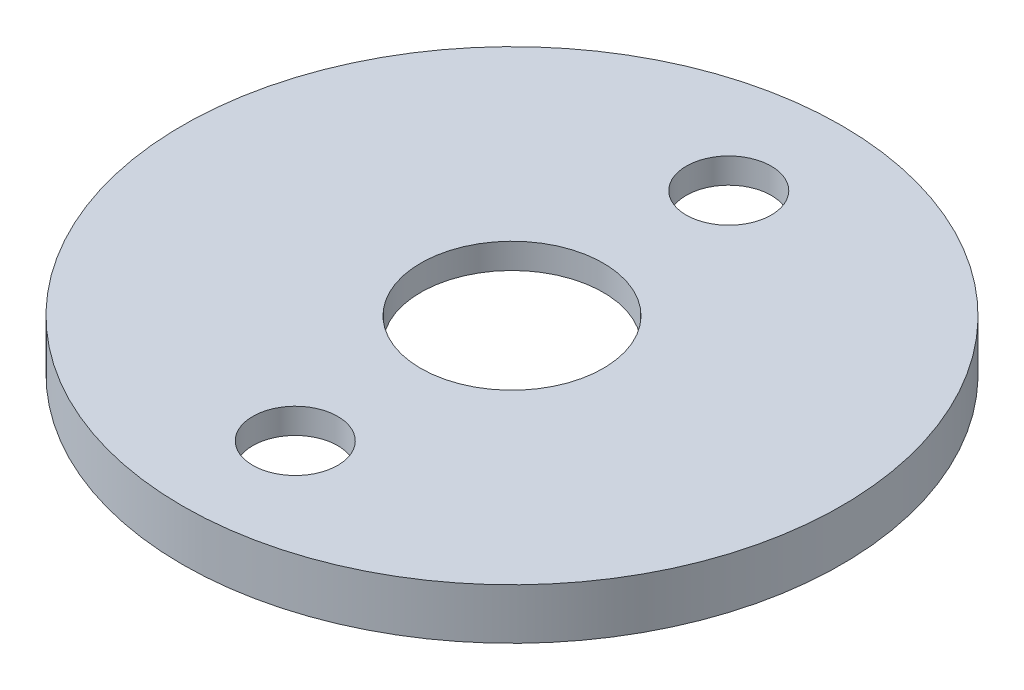
SolidWorks part; units mm, degrees
ref_plane "Front Plane" through (0, 0, 0) normal (0, 0, 1) x (1, 0, 0)
ref_plane "Top Plane" through (0, 0, 0) normal (0, 1, 0) x (1, 0, 0)
ref_plane "Right Plane" through (0, 0, 0) normal (1, 0, 0) x (0, 0, -1)
sketch "Sketch1" plane through (0, 0, 0) normal (0, 1, 0) x (1, 0, 0)
  circle A0 centre (0, 0) radius 12.5
  dimension "D1" = 25
extrude "Boss-Extrude1" add sketch "Sketch1" along normal blind 1
sketch "Sketch2" plane through (0, 1, 0) normal (0, 1, 0) x (1, 0, 0)
  line L0 (0, -12.5) -> (0, 12.5) construction
  line L1 (-5.7892, 6.875) -> (5.7892, 6.875)
  line L2 (-5.7892, -6.875) -> (5.7892, -6.875)
  line L3 (-5.0195, 10.225) -> (5.0195, 10.225)
  line L4 (-5.5215, -10.225) -> (5.5215, -10.225)
  circle A0 centre (0, 0) radius 12.5 construction
  circle A1 centre (0, 8.55) radius 1.675
  circle A2 centre (0, -8.55) radius 1.675
  circle A3 centre (0, 0) radius 3.6
  point P12 (0, 6.875)
  point P17 (0, -6.875)
  point P20 (0, 10.225)
  point P23 (0, -10.225)
  dimension "D1" = 3.35
  dimension "D2" = 3.35
  dimension "D3" = 1.675
  dimension "D5" = 13.75
  dimension "D6" = 7.2
  dimension "D4" = 1.675
  dimension "D7" = 3.35
  dimension "D8" = 3.35
  dimension "D9" = 6.875
extrude "Cut-Extrude1" cut sketch "Sketch2" against normal blind 1 contours A1 | A2 | A3
sketch "Sketch3" plane through (0, 1, 0) normal (0, 1, 0) x (1, 0, 0)
  circle A0 centre (0, 0) radius 13
  circle A1 centre (0, 0) radius 12.5
  dimension "D1" = 26
  dimension "D2" = 25
extrude "Boss-Extrude3" add sketch "Sketch3" against normal blind 2
sketch "Sketch5" plane through (0, -1, 0) normal (0, -1, 0) x (1, 0, 0)
  circle A0 centre (0, 0) radius 12.6
  dimension "D1" = 25.2
extrude "Cut-Extrude2" cut sketch "Sketch5" against normal blind 1
